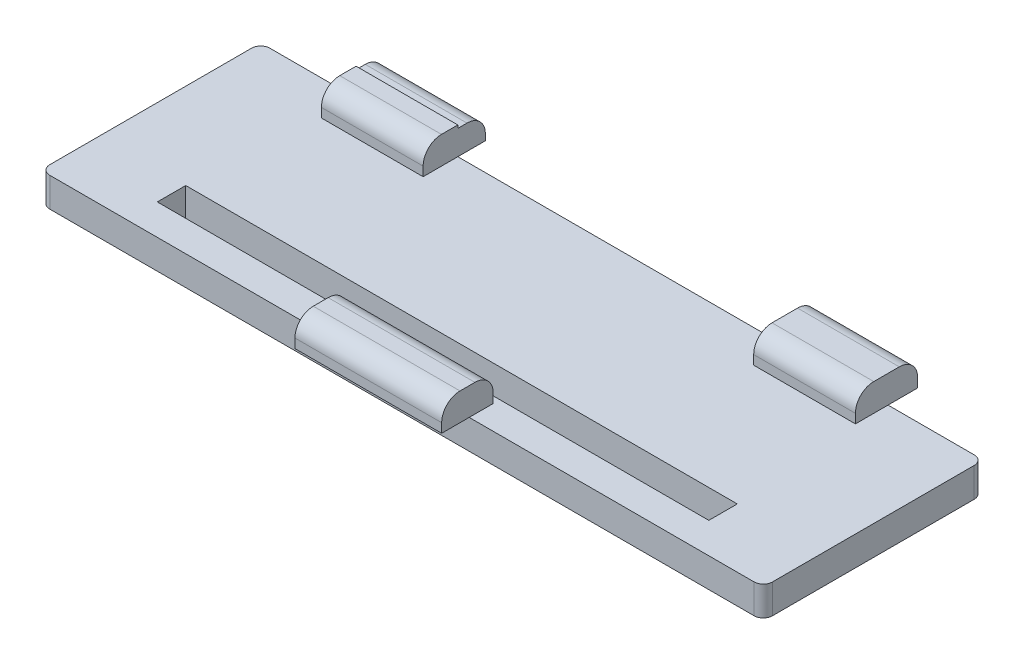
SolidWorks part; units mm, degrees
ref_plane "Front Plane" through (0, 0, 0) normal (0, 0, 1) x (1, 0, 0)
ref_plane "Top Plane" through (0, 0, 0) normal (0, 1, 0) x (1, 0, 0)
ref_plane "Right Plane" through (0, 0, 0) normal (1, 0, 0) x (0, 0, -1)
sketch "Sketch1" plane through (0, 0, 0) normal (0, 1, 0) x (1, 0, 0)
  line L1 (-23.4238, 6.8503) -> (15.9762, 6.8503)
  line L2 (-23.4238, 6.8503) -> (-23.4238, -5.1497)
  line L3 (-23.4238, -5.1497) -> (15.9762, -5.1497)
  line L4 (15.9762, 6.8503) -> (15.9762, -5.1497)
  line L5 (-18.7337, -1.9267) -> (11.3347, -1.9267)
  line L6 (-18.7337, -1.9267) -> (-18.7337, -3.4781)
  line L7 (-18.7337, -3.4781) -> (11.3347, -3.4781)
  line L8 (11.3347, -1.9267) -> (11.3347, -3.4781)
  point P8 (10.6377, -2.7771)
  point P9 (-19.4307, -2.2752)
  dimension "D1" = 12
  dimension "D2" = 39.4
extrude "Boss-Extrude2" add sketch "Sketch1" along normal blind 1.6
sketch "Sketch2" plane through (0, 1.6, 0) normal (0, 1, 0) x (1, 0, 0)
  line L0 (-23.4238, -5.1497) -> (15.9762, -5.1497) construction
  line L1 (-8.0586, -3.8377) -> (-0.0586, -3.8377) construction
  line L2 (-8.0586, -3.8377) -> (-8.0586, -5.1497) construction
  line L3 (-8.0586, -5.1497) -> (-0.0586, -5.1497) construction
  line L4 (-0.0586, -3.8377) -> (-0.0586, -5.1497) construction
  line L5 (15.9762, 6.8503) -> (-23.4238, 6.8503) construction
  line L6 (-18.2238, 6.8503) -> (-12.6775, 6.8503)
  line L7 (-18.2238, 6.8503) -> (-18.2238, 4.9587)
  line L8 (-18.2238, 4.9587) -> (-12.6775, 4.9587)
  line L9 (-12.6775, 6.8503) -> (-12.6775, 4.9587)
  line L10 (5.231, 6.9637) -> (10.7774, 6.9637)
  line L11 (5.231, 6.9637) -> (5.231, 5.0722)
  line L12 (5.231, 5.0722) -> (10.7774, 5.0722)
  line L13 (10.7774, 6.9637) -> (10.7774, 5.0722)
  line L14 (-3.7703, -5.1497) -> (-3.7238, 6.8503) construction
  line L16 (-8.0586, -5.1497) -> (-0.0586, -5.1497)
  line L17 (-8.0586, -5.1497) -> (-8.0586, -3.8377)
  line L18 (-8.0586, -3.8377) -> (-0.0586, -3.8377)
  line L19 (-0.0586, -5.1497) -> (-0.0586, -3.8377)
  dimension "D1" = 8
  dimension "D2" = 5.2
  dimension "D3" = 5.2
extrude "Boss-Extrude4" add sketch "Sketch2" along normal blind 1.5 contours L10 L13 L12 L11 | L17 L16 L19 L18 | L7 L6 L9 L8
sketch "Sketch5" plane through (0, 0, -6.8503) normal (0, 0, -1) x (-1, 0, 0)
  line L0 (12.6775, 3.1) -> (12.6775, 1.6) construction
  line L1 (12.6775, 1.6) -> (18.2238, 1.6)
  line L2 (12.6775, 1.6) -> (12.6775, 2.9377)
  line L3 (12.6775, 2.9377) -> (18.2238, 2.9377)
  line L4 (18.2238, 1.6) -> (18.2238, 2.9377)
  line L5 (18.2238, 3.1) -> (18.2238, 1.6) construction
  point P8 (22.9582, -5.0047)
extrude "Boss-Extrude5" add sketch "Sketch5" along normal blind 1.5
sketch "Sketch7" plane through (0, 0, -6.9637) normal (0, 0, -1) x (-1, 0, 0)
  line L0 (-5.231, 1.6) -> (12.6775, 1.6) construction
  line L1 (-10.7774, 3.1) -> (-5.231, 3.1)
  line L2 (-10.7774, 3.1) -> (-10.7774, 1.6)
  line L3 (-10.7774, 1.6) -> (-5.231, 1.6)
  line L4 (-5.231, 3.1) -> (-5.231, 1.6)
  line L5 (-5.231, 1.6) -> (-10.7774, 1.6) construction
extrude "Boss-Extrude6" add sketch "Sketch7" along normal blind 1.5
ref_plane "Plane1" through (-0.0586, 1.6, 5.1497) normal (1, 0, 0) x (0, 0, -1)
sketch "Sketch9" plane through (0, 0, 5.1497) normal (0, 0, 1) x (1, 0, 0)
  line L0 (-8.0586, 3.1) -> (-0.0586, 3.1) construction
  line L1 (-8.0586, 3.1) -> (-0.0586, 3.1)
  line L2 (-8.0586, 3.1) -> (-8.0586, 1.6)
  line L3 (-8.0586, 1.6) -> (-0.0586, 1.6)
  line L4 (-0.0586, 3.1) -> (-0.0586, 1.6)
  line L5 (-8.0586, 3.1) -> (-8.0586, 1.6) construction
  line L6 (-0.0586, -2.8096) -> (-0.0586, 6.0096) construction
  line L7 (-0.0586, 1.6) -> (15.9762, 1.6) construction
extrude "Boss-Extrude7" add sketch "Sketch9" along normal blind 1.5
fillet "Fillet3" radius 1 1 edges at (-4.0586, 3.1, 6.6497)
fillet "Fillet4" radius 1 2 edges at (-15.4507, 2.9377, -8.3503) (8.0042, 3.1, -8.4637)
fillet "Fillet5" radius 1 2 edges at (-15.4507, 3.1, -4.9587) (8.0042, 3.1, -5.0722)
fillet "Fillet6" radius 1 1 edges at (-4.0586, 3.1, 3.8377)
fillet "Fillet7" radius 0.5 4 edges at (-23.4238, 0.8, -6.8503) (-23.4238, 0.8, 5.1497) (15.9762, 0.8, 5.1497) (15.9762, 0.8, -6.8503)
